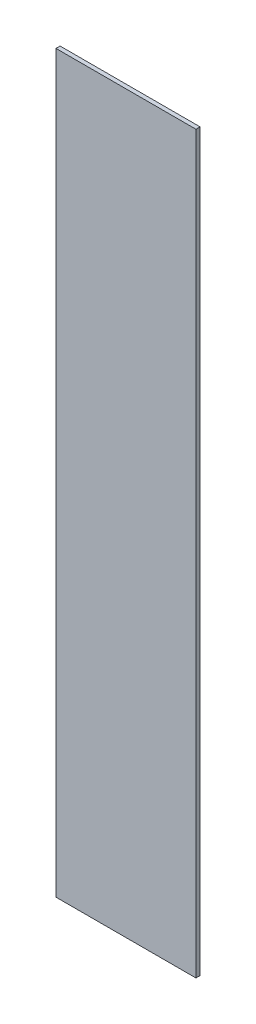
SolidWorks part; units mm, degrees
ref_plane "Front Plane" through (0, 0, 0) normal (0, 0, 1) x (1, 0, 0)
ref_plane "Top Plane" through (0, 0, 0) normal (0, 1, 0) x (1, 0, 0)
ref_plane "Right Plane" through (0, 0, 0) normal (1, 0, 0) x (0, 0, -1)
sketch "Sketch1" plane through (0, 0, 0) normal (0, 0, 1) x (1, 0, 0)
  line L1 (50.8, 266.7) -> (-50.8, 266.7)
  line L2 (50.8, 266.7) -> (50.8, -266.7)
  line L3 (50.8, -266.7) -> (-50.8, -266.7)
  line L4 (-50.8, 266.7) -> (-50.8, -266.7)
  line L5 (50.8, 266.7) -> (-50.8, -266.7) construction
  line L6 (50.8, -266.7) -> (-50.8, 266.7) construction
  point P0 (0, 0)
  dimension "D1" = 101.6
  dimension "D2" = 533.4
extrude "Boss-Extrude1" add sketch "Sketch1" along normal blind 2.9972
